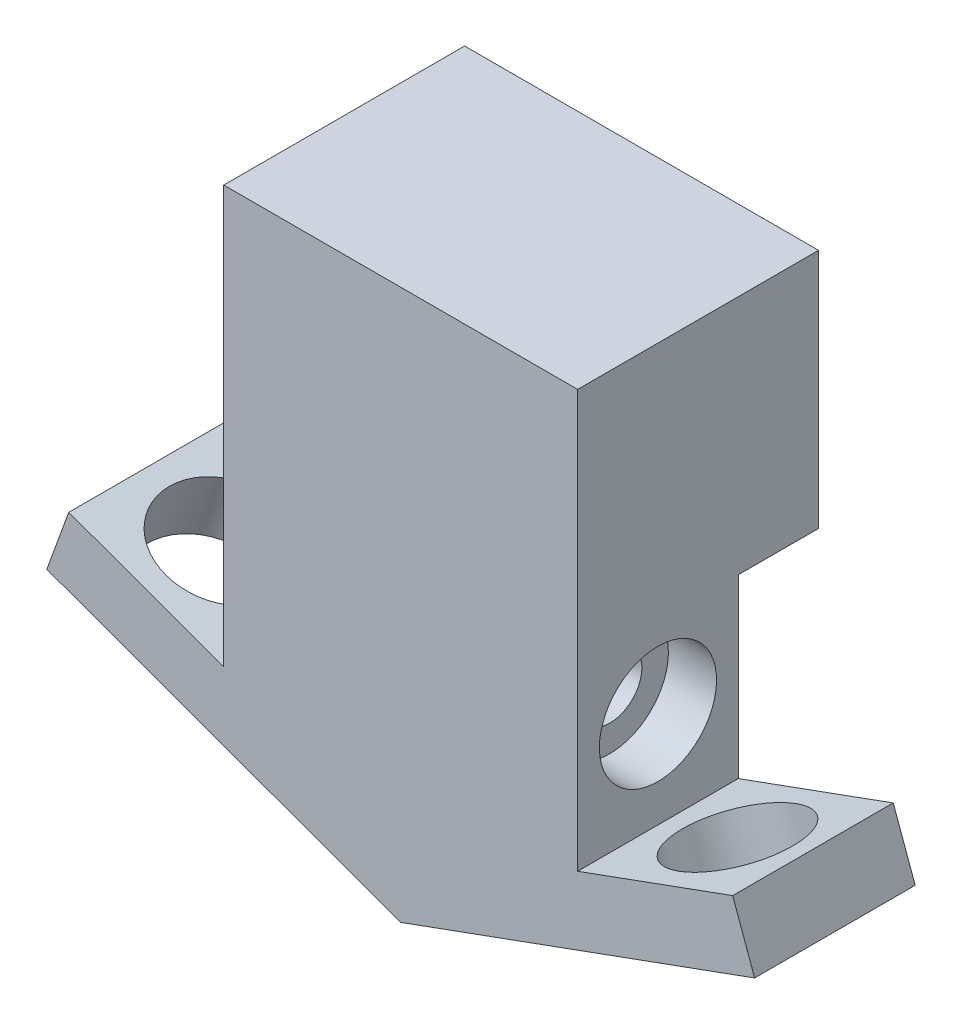
SolidWorks part; units mm, degrees
ref_plane "Front Plane" through (0, 0, 0) normal (0, 0, 1) x (1, 0, 0)
ref_plane "Top Plane" through (0, 0, 0) normal (0, 1, 0) x (1, 0, 0)
ref_plane "Right Plane" through (0, 0, 0) normal (1, 0, 0) x (0, 0, -1)
sketch "Sketch1" plane through (0, 0, 0) normal (0, 0, 1) x (1, 0, 0)
  line L0 (0, 0) -> (20.6732, 7.5244)
  line L1 (20.6732, 7.5244) -> (22.0413, 3.7657)
  line L2 (22.0413, 3.7657) -> (0, -4.2567)
  line L6 (0, 0) -> (0, 14.7361) construction
  line L7 (-22.0413, 3.7657) -> (0, -4.2567)
  line L8 (-20.6732, 7.5244) -> (-22.0413, 3.7657)
  line L9 (0, 0) -> (-20.6732, 7.5244)
  point P6 (0, -4.2862)
  dimension "D1" = 70
  dimension "D2" = 4
  dimension "D3" = 22
extrude "Boss-Extrude1" add sketch "Sketch1" along normal blind 10
sketch "Sketch2" plane through (0, 0, 0) normal (-0.342, 0.9397, 0) x (0.9397, 0.342, 0)
  line L0 (22, -10) -> (22, 0) construction
  line L1 (0, -10) -> (0, 0) construction
  circle A0 centre (17, -5) radius 3.65
  point P4 (22, -5)
  dimension "D1" = 7.3
  dimension "D2" = 17
extrude "Cut-Extrude1" cut sketch "Sketch2" against normal up to surface (16.4236 mm away)
mirror "Mirror1" about plane through (0, 0, 0) normal (1, 0, 0) of "Cut-Extrude1"
sketch "Sketch3" plane through (0, 0, 10) normal (0, 0, 1) x (1, 0, 0)
  line L0 (0, -4.2567) -> (-11.0207, -0.2455)
  line L1 (-22.0413, 3.7657) -> (0, -4.2567) construction
  line L2 (-11.0207, -0.2455) -> (-11.0207, 15)
  line L3 (-11.0207, 15) -> (11.0207, 15)
  line L4 (11.0207, 15) -> (11.0207, -0.2455)
  line L5 (0, -4.2567) -> (22.0413, 3.7657) construction
  line L6 (11.0207, -0.2455) -> (0, -4.2567)
  point P5 (11.0207, -16.0636)
  dimension "D1" = 15
extrude "Boss-Extrude3" add sketch "Sketch3" against normal up to surface (10 mm away) up to face at (0, 3.0539, 0)
sketch "Sketch6" plane through (11.0207, 0, 0) normal (1, 0, 0) x (0, 0, -1)
  line L0 (0, 15) -> (-10, 15) construction
  circle A0 centre (-5, 10) radius 3.65
  point P4 (-5, 15)
  dimension "D1" = 7.3
  dimension "D2" = 5
extrude "Cut-Extrude4" cut sketch "Sketch6" against normal blind 3
mirror "Mirror3" about plane through (0, 0, 0) normal (1, 0, 0) of "Cut-Extrude4"
sketch "Sketch8" plane through (-8.0207, 0, 0) normal (-1, 0, 0) x (0, 0, 1)
  circle A0 centre (5, 10) radius 2
  dimension "D1" = 4
extrude "Cut-Extrude5" cut sketch "Sketch8" against normal up to surface (16.0413 mm away) up to face at (8.0207, 13.65, 5)
sketch "Sketch9" plane through (-11.0207, 0, 0) normal (-1, 0, 0) x (0, 0, 1)
  line L1 (10, 15) -> (-5, 15)
  line L2 (10, 15) -> (10, 30)
  line L3 (10, 30) -> (-5, 30)
  line L4 (-5, 15) -> (-5, 30)
  dimension "D1" = 15
  dimension "D2" = 15
extrude "Boss-Extrude4" add sketch "Sketch9" against normal up to surface (22.0413 mm away) up to face at (11.0207, 13.65, 5)
